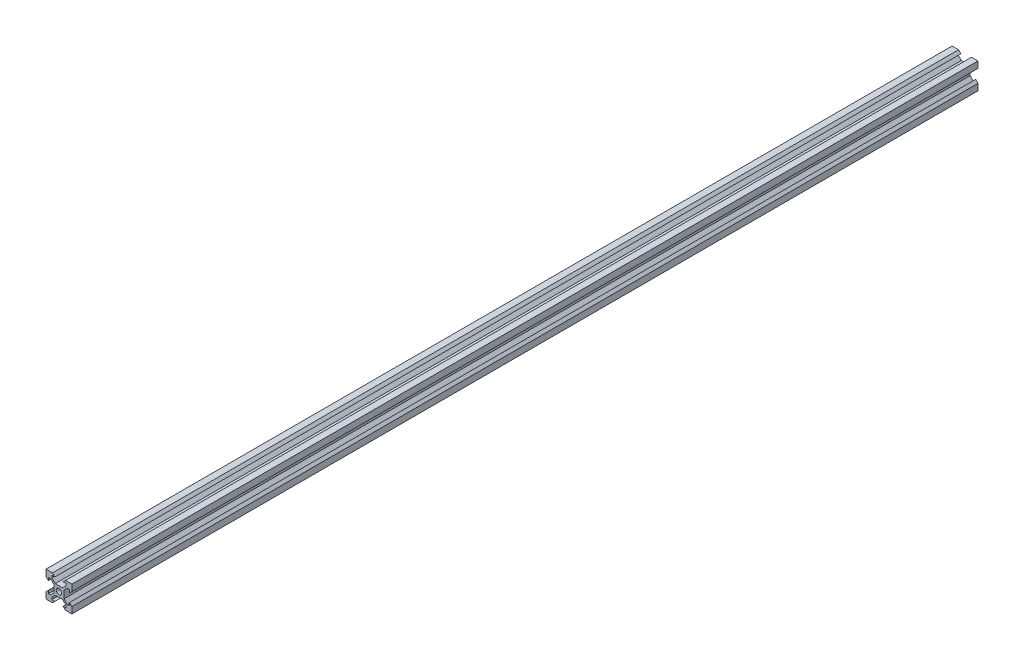
SolidWorks part; units mm, degrees
ref_plane "Front Plane" through (0, 0, 0) normal (0, 0, 1) x (1, 0, 0)
ref_plane "Top Plane" through (0, 0, 0) normal (0, 1, 0) x (1, 0, 0)
ref_plane "Right Plane" through (0, 0, 0) normal (1, 0, 0) x (0, 0, -1)
sketch "Sketch1" plane through (0, 0, 0) normal (0, 0, 1) x (1, 0, 0)
  line L0 (-10, 10) -> (-10, 5)
  line L1 (-10, 5) -> (-8.2, 3.2)
  line L2 (-8.2, 3.2) -> (-8.2, 5.4993)
  line L3 (-8.2, 5.4993) -> (-6.56, 5.4993)
  line L4 (-6.56, 5.4993) -> (-3.9007, 2.84)
  line L5 (-3.9007, 2.84) -> (-3.9007, -2.84)
  line L6 (-3.9007, -2.84) -> (-6.56, -5.4993)
  line L7 (-6.56, -5.4993) -> (-8.2, -5.4993)
  line L8 (-8.2, -5.4993) -> (-8.2, -3.2)
  line L9 (-8.2, -3.2) -> (-10, -5)
  line L10 (-10, -5) -> (-10, -10)
  line L11 (-10, -10) -> (-5, -10)
  line L12 (-5, -10) -> (-3.2, -8.2)
  line L13 (-3.2, -8.2) -> (-5.4993, -8.2)
  line L14 (-5.4993, -8.2) -> (-5.4993, -6.56)
  line L15 (-5.4993, -6.56) -> (-2.84, -3.9007)
  line L16 (-2.84, -3.9007) -> (2.84, -3.9007)
  line L17 (2.84, -3.9007) -> (5.4993, -6.56)
  line L18 (5.4993, -6.56) -> (5.4993, -8.2)
  line L19 (5.4993, -8.2) -> (3.2, -8.2)
  line L20 (3.2, -8.2) -> (5, -10)
  line L21 (5, -10) -> (10, -10)
  line L22 (10, -10) -> (10, -5)
  line L23 (10, -5) -> (8.2, -3.2)
  line L24 (8.2, -3.2) -> (8.2, -5.4993)
  line L25 (8.2, -5.4993) -> (6.56, -5.4993)
  line L26 (6.56, -5.4993) -> (3.9007, -2.84)
  line L27 (3.9007, -2.84) -> (3.9007, 2.84)
  line L28 (3.9007, 2.84) -> (6.56, 5.4993)
  line L29 (6.56, 5.4993) -> (8.2, 5.4993)
  line L30 (8.2, 5.4993) -> (8.2, 3.2)
  line L31 (8.2, 3.2) -> (10, 5)
  line L32 (10, 5) -> (10, 10)
  line L33 (10, 10) -> (5, 10)
  line L34 (5, 10) -> (3.2, 8.2)
  line L35 (3.2, 8.2) -> (5.4993, 8.2)
  line L36 (5.4993, 8.2) -> (5.4993, 6.56)
  line L37 (5.4993, 6.56) -> (2.84, 3.9007)
  line L38 (2.84, 3.9007) -> (-2.84, 3.9007)
  line L39 (-2.84, 3.9007) -> (-5.4993, 6.56)
  line L40 (-5.4993, 6.56) -> (-5.4993, 8.2)
  line L41 (-5.4993, 8.2) -> (-3.2, 8.2)
  line L42 (-3.2, 8.2) -> (-5, 10)
  line L43 (-5, 10) -> (-10, 10)
  circle A0 centre (0, 0) radius 2.1
extrude "Boss-Extrude1" add sketch "Sketch1" against normal blind 700
